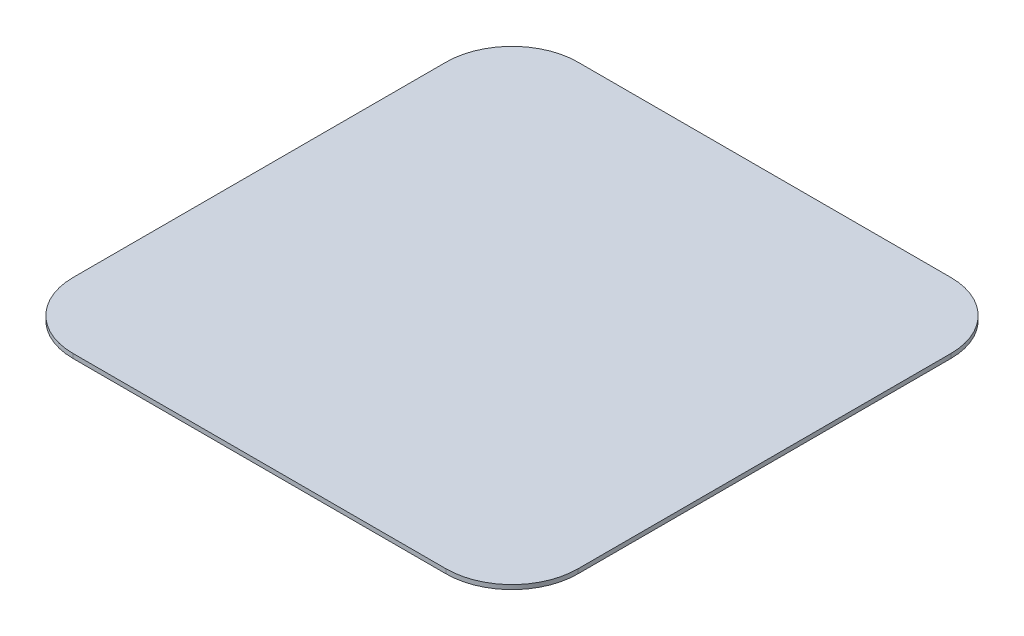
SolidWorks part; units mm, degrees
ref_plane "Front Plane" through (0, 0, 0) normal (0, 0, 1) x (1, 0, 0)
ref_plane "Top Plane" through (0, 0, 0) normal (0, 1, 0) x (1, 0, 0)
ref_plane "Right Plane" through (0, 0, 0) normal (1, 0, 0) x (0, 0, -1)
sketch "Sketch1" plane through (0, 0, 0) normal (0, 1, 0) x (1, 0, 0)
  line L1 (-115, 115) -> (115, 115)
  line L2 (-115, 115) -> (-115, -115)
  line L3 (-115, -115) -> (115, -115)
  line L4 (115, 115) -> (115, -115)
  line L5 (-115, 115) -> (115, -115) construction
  line L6 (-115, -115) -> (115, 115) construction
  point P0 (0, 0)
  dimension "D1" = 230
  dimension "D2" = 230
extrude "Boss-Extrude1" add sketch "Sketch1" along normal blind 2
fillet "Fillet1" radius 30 4 edges at (-115, 1, -115) (-115, 1, 115) (115, 1, -115) (115, 1, 115)
